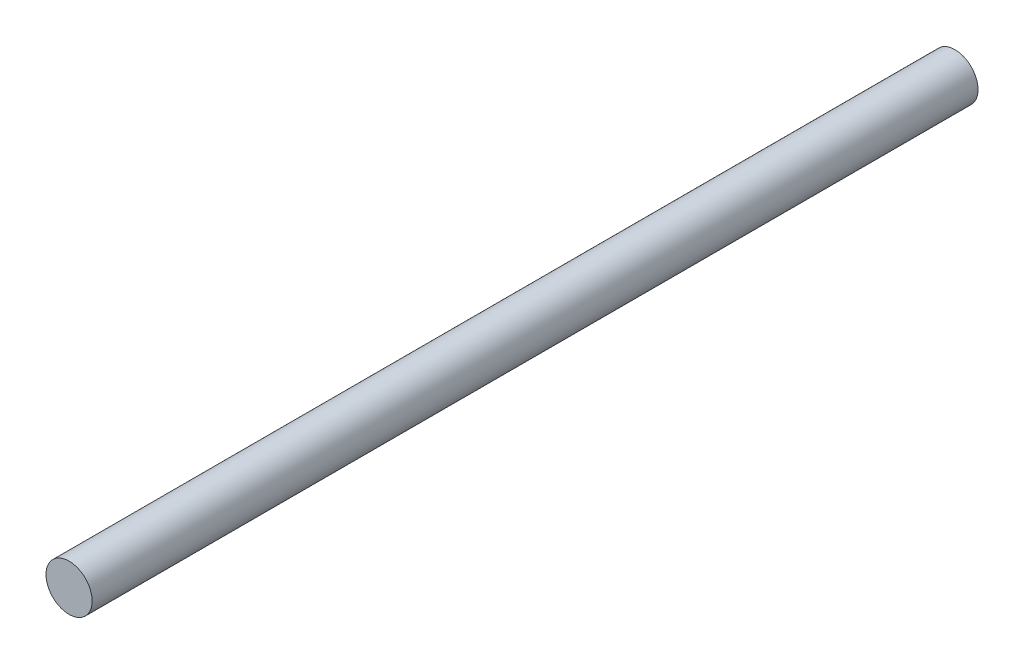
SolidWorks part; units mm, degrees
ref_plane "Front Plane" through (0, 0, 0) normal (0, 0, 1) x (1, 0, 0)
ref_plane "Top Plane" through (0, 0, 0) normal (0, 1, 0) x (1, 0, 0)
ref_plane "Right Plane" through (0, 0, 0) normal (1, 0, 0) x (0, 0, -1)
sketch "Sketch1" plane through (0, 0, 0) normal (0, 0, 1) x (1, 0, 0)
  circle A0 centre (0, 0) radius 3.9688
  point P4 (-3.9688, 0)
  dimension "Diameter" = 7.9375
sketch "Sketch2" plane through (0, 0, 0) normal (1, 0, 0) x (0, 0, -1)
  line L0 (-76.2, 0) -> (76.2, 0)
  line L1 (0, -3.9688) -> (0, 3.9688) construction
  line L2 (0, 3.9688) -> (0, -3.9688) construction
  line L3 (76.2, -3.9688) -> (76.2, 3.9687)
  line L4 (-76.2, -3.9688) -> (-76.2, 3.9687)
  point P0 (68.2625, 0)
  point P4 (0, 0)
  point P6 (-68.2625, 0)
  point P12 (0, 0)
  point P15 (76.2, 0)
  point P18 (-76.2, 0)
  dimension "D1" = 7.9375
  dimension "Length" = 152.4
sketch "Sketch3" plane through (0, 0, 0) normal (0, 0, 1) x (1, 0, 0)
  circle A1 centre (0, 0) radius 3.9688
  circle A5 centre (0, 0) radius 3.9688
  dimension "D1" = 0
extrude "Boss-Extrude1" add sketch "Sketch3" along normal mid plane 152.4
equation "\"D1@Boss-Extrude1\"=\"Length@Sketch2\""
equation "\"D1@Sketch2\"=\"Diameter@Sketch1\""
